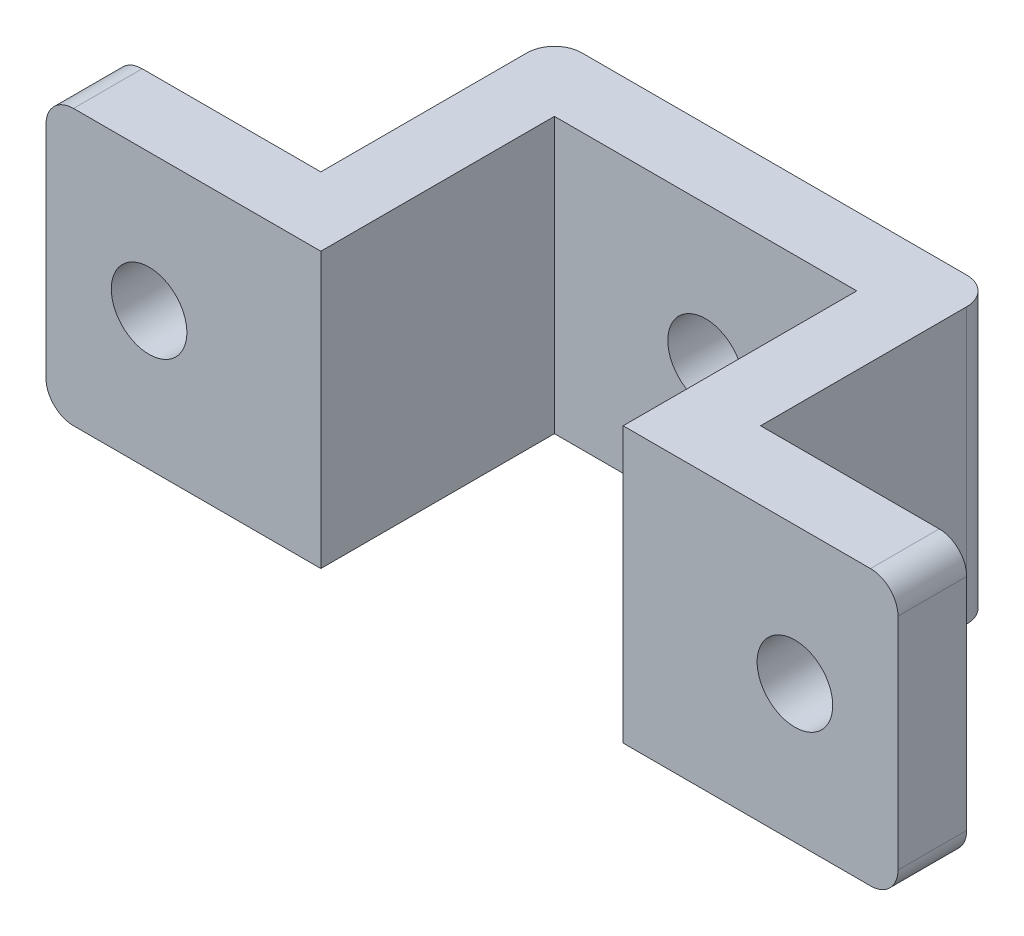
SolidWorks part; units mm, degrees
ref_plane "前视基准面" through (0, 0, 0) normal (0, 0, 1) x (1, 0, 0)
ref_plane "上视基准面" through (0, 0, 0) normal (0, 1, 0) x (1, 0, 0)
ref_plane "右视基准面" through (0, 0, 0) normal (1, 0, 0) x (0, 0, -1)
sketch "草图1" plane through (0, 0, 0) normal (0, 1, 0) x (1, 0, 0)
  line L1 (-12.058, 6.2222) -> (19.942, 6.2222)
  line L2 (-12.058, 6.2222) -> (-12.058, -15.7778)
  line L3 (-12.058, -15.7778) -> (-7.058, -15.7778)
  line L4 (19.942, 6.2222) -> (19.942, -15.7778)
  line L5 (-12.058, 6.2222) -> (3.942, -4.7778) construction
  line L6 (-12.058, -15.7778) -> (-7.058, -12.3403) construction
  line L7 (-7.058, 1.2222) -> (14.942, 1.2222)
  line L8 (14.942, 1.2222) -> (14.942, -10.7778)
  line L10 (-7.058, 1.2222) -> (-7.058, -10.7778)
  line L11 (-7.058, -10.7778) -> (-7.058, -15.7778)
  line L12 (14.942, -10.7778) -> (14.942, -15.7778)
  line L14 (-7.058, -10.7778) -> (14.942, -10.7778) construction
  line L15 (14.942, -15.7778) -> (19.942, -15.7778)
  line L16 (-12.058, -15.7778) -> (19.942, -15.7778) construction
  line L17 (3.942, -4.7778) -> (19.942, 6.2222) construction
  line L18 (14.942, -12.3403) -> (19.942, -15.7778) construction
  point P4 (3.942, -4.7778)
  dimension "D1" = 32
  dimension "D2" = 22
  dimension "D3" = 5
extrude "凸台-拉伸1" add sketch "草图1" along normal blind 20
sketch "草图2" plane through (0, 0, -6.2222) normal (0, 0, -1) x (-1, 0, 0)
  line L0 (-19.942, 10) -> (12.058, 10) construction
  line L1 (-19.942, 20) -> (-19.942, 0) construction
  line L2 (12.058, 20) -> (12.058, 0) construction
  circle A0 centre (-3.942, 10) radius 2.75
  dimension "D1" = 5.5
extrude "切除-拉伸1" cut sketch "草图2" against normal through all
sketch "草图3" plane through (-12.058, 0, 0) normal (-1, 0, 0) x (0, 0, 1)
  line L0 (10.7778, 0) -> (10.7778, 20)
  line L1 (-6.2222, 0) -> (15.7778, 0) construction
  line L2 (-6.2222, 20) -> (15.7778, 20) construction
  line L3 (10.7778, 20) -> (15.7778, 20)
  line L4 (15.7778, 20) -> (15.7778, 0)
  line L5 (15.7778, 0) -> (10.7778, 0)
  dimension "D1" = 5
extrude "凸台-拉伸2" add sketch "草图3" along normal blind 15
ref_plane "基准面1" through (3.942, 0, 0) normal (1, 0, 0) x (0, 0, -1)
sketch "草图4" plane through (0, 0, 10.7778) normal (0, 0, -1) x (-1, 0, 0)
  line L0 (19.558, 20) -> (19.558, 0) construction
  line L1 (27.058, 20) -> (12.058, 20) construction
  line L2 (27.058, 0) -> (12.058, 0) construction
  circle A0 centre (19.558, 10) radius 2.75
  dimension "D1" = 5.5
extrude "切除-拉伸2" cut sketch "草图4" against normal through all
ref_plane "基准面2" through (3.942, 0, 0) normal (-1, 0, 0) x (0, 0, 1)
ref_plane "基准面3" through (3.942, 0, 0) normal (-1, 0, 0) x (0, 0, 1)
ref_plane "基准面4" through (3.942, 0, 0) normal (-1, 0, 0) x (0, 0, 1)
mirror "镜向5" about plane through (3.942, 0, 0) normal (-1, 0, 0) of "切除-拉伸2", "凸台-拉伸2"
fillet "圆角1" radius 2 6 edges at (34.942, 0, 13.2778) (34.942, 20, 13.2778) (19.942, 10, -6.2222) (-27.058, 0, 13.2778) (-27.058, 20, 13.2778) (-12.058, 10, -6.2222)
sketch "草图5" plane through (0, 0, -6.2222) normal (0, 0, -1) x (-1, 0, 0)
  circle A0 centre (-3.942, 10) radius 2.75
  circle A1 centre (-3.942, 10) radius 6
  dimension "D1" = 12
extrude "凸台-拉伸4" add sketch "草图5" along normal blind 3
